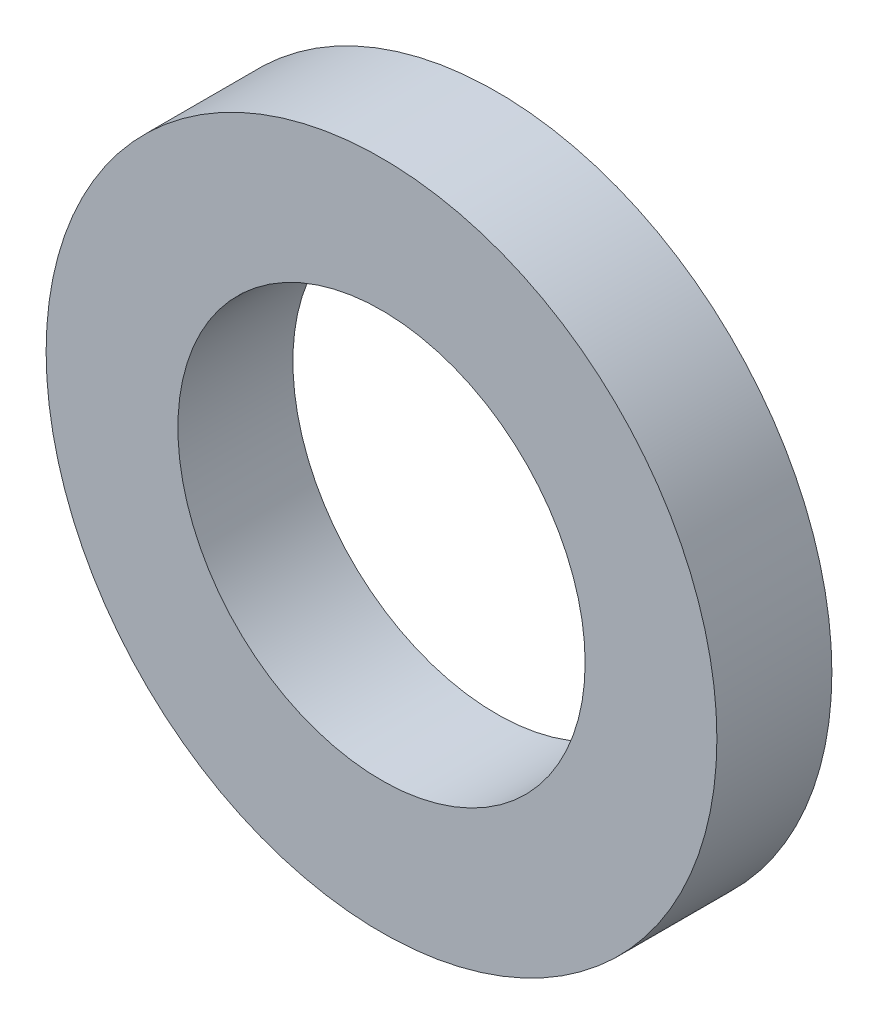
SolidWorks part; units mm, degrees
ref_plane "Front Plane" through (0, 0, 0) normal (0, 0, 1) x (1, 0, 0)
ref_plane "Top Plane" through (0, 0, 0) normal (0, 1, 0) x (1, 0, 0)
ref_plane "Right Plane" through (0, 0, 0) normal (1, 0, 0) x (0, 0, -1)
sketch "Sketch2" plane through (0, 0, 0) normal (0, 0, 1) x (1, 0, 0)
  circle A0 centre (0, 0) radius 4.25
  circle A1 centre (0, 0) radius 7
  dimension "D1" = 8.5
  dimension "D2" = 14
extrude "Boss-Extrude1" add sketch "Sketch2" along normal blind 2.4
